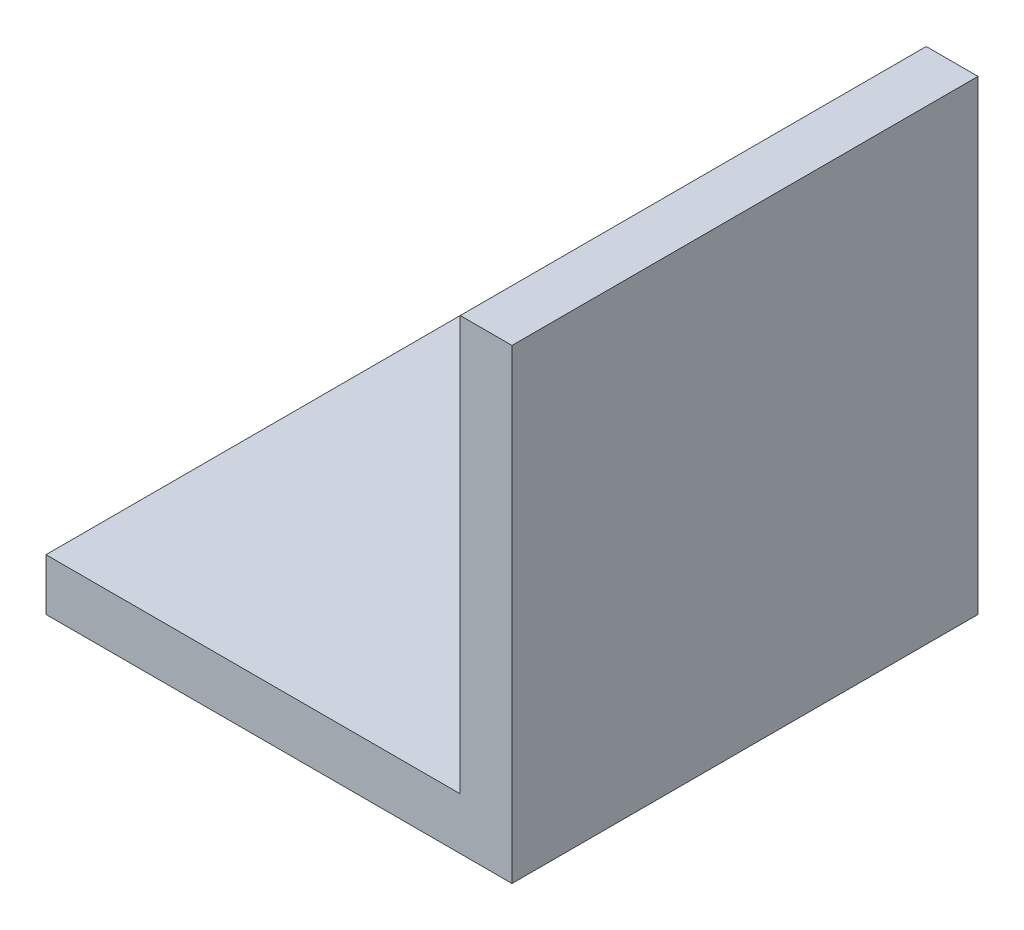
SolidWorks part; units mm, degrees
ref_plane "Front Plane" through (0, 0, 0) normal (0, 0, 1) x (1, 0, 0)
ref_plane "Top Plane" through (0, 0, 0) normal (0, 1, 0) x (1, 0, 0)
ref_plane "Right Plane" through (0, 0, 0) normal (1, 0, 0) x (0, 0, -1)
sketch "Sketch1" plane through (0, 0, 0) normal (0, 1, 0) x (1, 0, 0)
  line L2 (-49.4299, -37.5879) -> (26.7701, -37.5879)
  line L3 (-49.4299, -37.5879) -> (-49.4299, 38.6121)
  line L4 (-49.4299, 38.6121) -> (26.7701, 38.6121)
  line L5 (26.7701, -37.5879) -> (26.7701, 38.6121)
  dimension "D1" = 76.2
  dimension "D2" = 76.2
extrude "Boss-Extrude1" add sketch "Sketch1" along normal blind 8.4667
sketch "Sketch2" plane through (26.7701, 0, 0) normal (1, 0, 0) x (0, 0, -1)
  line L1 (-37.5879, 0) -> (38.6121, 0)
  line L2 (-37.5879, 0) -> (-37.5879, 76.2)
  line L3 (-37.5879, 76.2) -> (38.6121, 76.2)
  line L4 (38.6121, 0) -> (38.6121, 76.2)
  dimension "D1" = 76.2
  dimension "D2" = 76.2
extrude "Boss-Extrude2" add sketch "Sketch2" against normal blind 8.4667
